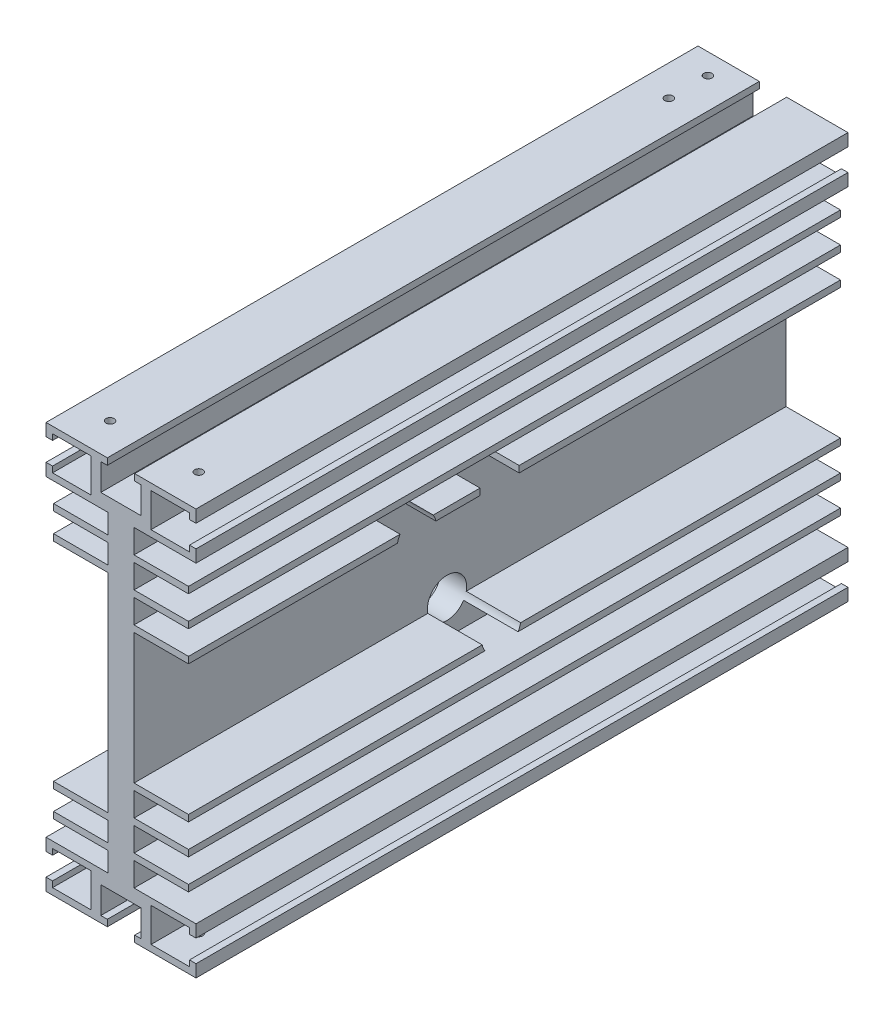
SolidWorks part; units mm, degrees
material "Alumina"
ref_plane "Plano frontal" through (0, 0, 0) normal (0, 0, 1) x (1, 0, 0)
ref_plane "Plano superior" through (0, 0, 0) normal (0, 1, 0) x (1, 0, 0)
ref_plane "Plano direito" through (0, 0, 0) normal (1, 0, 0) x (0, 0, -1)
sketch "Esboço1" plane through (0, 0, 0) normal (0, 0, 1) x (1, 0, 0)
  line L0 (-54.7403, -0.6) -> (-54.7403, 63.2)
  line L1 (-44.5403, -20.8) -> (-44.5403, -29)
  line L2 (-44.5403, -29) -> (-46.5403, -29)
  line L3 (-46.5403, -29) -> (-46.5403, -31)
  line L4 (-46.5403, -31) -> (-27.7403, -31)
  line L5 (-27.7403, -31) -> (-27.7403, -27.2)
  line L6 (-27.7403, -27.2) -> (-29.7403, -27.2)
  line L7 (-29.7403, -27.2) -> (-29.7403, -29)
  line L8 (-29.7403, -29) -> (-41.5403, -29)
  line L9 (-41.5403, -29) -> (-41.5403, -18.6)
  line L10 (-41.5403, -18.6) -> (-29.7403, -18.6)
  line L11 (-29.7403, -18.6) -> (-29.7403, -20.4)
  line L12 (-29.7403, -20.4) -> (-27.7403, -20.4)
  line L13 (-27.7403, -20.4) -> (-27.7403, -16.6)
  line L14 (-27.7403, -16.6) -> (-46.7403, -16.6)
  line L15 (-46.7403, -7.3) -> (-46.7403, 0)
  line L16 (-46.7403, -7.3) -> (-30.0403, -7.3)
  line L17 (-30.0403, -7.3) -> (-30.0403, -9.3)
  line L18 (-30.0403, -9.3) -> (-46.7403, -9.3)
  line L19 (-46.7403, -16.6) -> (-46.7403, -9.3)
  line L20 (-46.7403, 0) -> (-30.0403, 0)
  line L21 (-30.0403, 0) -> (-30.0403, 2)
  line L22 (-30.0403, 2) -> (-46.7403, 2)
  line L23 (-46.7403, 2) -> (-46.7403, 9.3)
  line L24 (-46.7403, 9.3) -> (-30.0403, 9.3)
  line L25 (-30.0403, 9.3) -> (-30.0403, 11.3)
  line L26 (-30.0403, 11.3) -> (-46.7403, 11.3)
  line L27 (-46.7403, 11.3) -> (-46.7403, 51.3)
  line L29 (-56.9403, -20.8) -> (-44.5403, -20.8)
  line L30 (-56.9403, 83.4) -> (-56.9403, 91.6)
  line L31 (-56.9403, 91.6) -> (-54.9403, 91.6)
  line L32 (-54.9403, 91.6) -> (-54.9403, 93.6)
  line L33 (-54.9403, 93.6) -> (-73.7403, 93.6)
  line L34 (-73.7403, 93.6) -> (-73.7403, 89.8)
  line L35 (-71.4403, -0.6) -> (-54.7403, -0.6)
  line L36 (-71.4403, -2.6) -> (-71.4403, -0.6)
  line L37 (-54.7403, -2.6) -> (-71.4403, -2.6)
  line L38 (-54.7403, -16.6) -> (-54.7403, -10.6)
  line L39 (-71.4403, -10.6) -> (-54.7403, -10.6)
  line L40 (-71.4403, -8.6) -> (-71.4403, -10.6)
  line L41 (-54.7403, -8.6) -> (-71.4403, -8.6)
  line L42 (-54.7403, -8.6) -> (-54.7403, -2.6)
  line L43 (-73.7403, -16.6) -> (-54.7403, -16.6)
  line L44 (-73.7403, -20.4) -> (-73.7403, -16.6)
  line L45 (-71.7403, -20.4) -> (-73.7403, -20.4)
  line L46 (-71.7403, -18.6) -> (-71.7403, -20.4)
  line L47 (-59.9403, -18.6) -> (-71.7403, -18.6)
  line L48 (-59.9403, -29) -> (-59.9403, -18.6)
  line L49 (-71.7403, -29) -> (-59.9403, -29)
  line L50 (-71.7403, -27.2) -> (-71.7403, -29)
  line L51 (-73.7403, -27.2) -> (-71.7403, -27.2)
  line L52 (-73.7403, -31) -> (-73.7403, -27.2)
  line L53 (-54.9403, -31) -> (-73.7403, -31)
  line L54 (-54.9403, -29) -> (-54.9403, -31)
  line L55 (-56.9403, -29) -> (-54.9403, -29)
  line L56 (-56.9403, -20.8) -> (-56.9403, -29)
  line L57 (-73.7403, 89.8) -> (-71.7403, 89.8)
  line L58 (-71.7403, 89.8) -> (-71.7403, 91.6)
  line L59 (-71.7403, 91.6) -> (-59.9403, 91.6)
  line L60 (-59.9403, 91.6) -> (-59.9403, 81.2)
  line L61 (-59.9403, 81.2) -> (-71.7403, 81.2)
  line L62 (-71.7403, 81.2) -> (-71.7403, 83)
  line L63 (-71.7403, 83) -> (-73.7403, 83)
  line L64 (-73.7403, 83) -> (-73.7403, 79.2)
  line L65 (-73.7403, 79.2) -> (-54.7403, 79.2)
  line L66 (-54.7403, 71.2) -> (-54.7403, 65.2)
  line L67 (-54.7403, 71.2) -> (-71.4403, 71.2)
  line L68 (-71.4403, 71.2) -> (-71.4403, 73.2)
  line L69 (-71.4403, 73.2) -> (-54.7403, 73.2)
  line L70 (-54.7403, 79.2) -> (-54.7403, 73.2)
  line L71 (-54.7403, 65.2) -> (-71.4403, 65.2)
  line L72 (-71.4403, 65.2) -> (-71.4403, 63.2)
  line L73 (-71.4403, 63.2) -> (-54.7403, 63.2)
  line L74 (-56.9403, 83.4) -> (-44.5403, 83.4)
  line L75 (-30.0403, 51.3) -> (-46.7403, 51.3)
  line L76 (-30.0403, 53.3) -> (-30.0403, 51.3)
  line L77 (-46.7403, 53.3) -> (-30.0403, 53.3)
  line L78 (-46.7403, 60.6) -> (-46.7403, 53.3)
  line L79 (-30.0403, 60.6) -> (-46.7403, 60.6)
  line L80 (-30.0403, 62.6) -> (-30.0403, 60.6)
  line L81 (-46.7403, 62.6) -> (-30.0403, 62.6)
  line L82 (-46.7403, 79.2) -> (-46.7403, 71.9)
  line L83 (-30.0403, 71.9) -> (-46.7403, 71.9)
  line L84 (-30.0403, 69.9) -> (-30.0403, 71.9)
  line L85 (-46.7403, 69.9) -> (-30.0403, 69.9)
  line L86 (-46.7403, 69.9) -> (-46.7403, 62.6)
  line L87 (-27.7403, 79.2) -> (-46.7403, 79.2)
  line L88 (-27.7403, 83) -> (-27.7403, 79.2)
  line L89 (-29.7403, 83) -> (-27.7403, 83)
  line L90 (-29.7403, 81.2) -> (-29.7403, 83)
  line L91 (-41.5403, 81.2) -> (-29.7403, 81.2)
  line L92 (-41.5403, 91.6) -> (-41.5403, 81.2)
  line L93 (-29.7403, 91.6) -> (-41.5403, 91.6)
  line L94 (-29.7403, 89.8) -> (-29.7403, 91.6)
  line L95 (-27.7403, 89.8) -> (-29.7403, 89.8)
  line L96 (-27.7403, 93.6) -> (-27.7403, 89.8)
  line L97 (-46.5403, 93.6) -> (-27.7403, 93.6)
  line L98 (-46.5403, 91.6) -> (-46.5403, 93.6)
  line L99 (-44.5403, 91.6) -> (-46.5403, 91.6)
  line L100 (-44.5403, 83.4) -> (-44.5403, 91.6)
  dimension "D1" = 2
  dimension "D2" = 3.8
  dimension "D3" = 2
  dimension "D4" = 18.8
  dimension "D5" = 3
  dimension "D6" = 2
  dimension "D7" = 2
  dimension "D8" = 2
  dimension "D9" = 3.8
  dimension "D10" = 4.2
  dimension "D11" = 19
  dimension "D12" = 16.7
  dimension "D13" = 7.3
  dimension "D14" = 2
  dimension "D15" = 6
  dimension "D16" = 6
  dimension "D17" = 10.4
  dimension "D18" = 40
  dimension "D19" = 63.8
extrude "Ressalto-extrusão1" add sketch "Esboço1" along normal blind 200
ref_plane "Plano1" through (0, 0, 100) normal (0, 0, 1) x (1, 0, 0)
ref_plane "Plano2" through (0, 31.3, 0) normal (0, -1, 0) x (1, 0, 0)
sketch "Esboço5" plane through (-54.7403, 0, 0) normal (-1, 0, 0) x (0, 0, 1)
  line L3 (200, 93.6) -> (0, 93.6) construction
  line L4 (0, 63.2) -> (0, -0.6) construction
  circle A0 centre (130, 50.1) radius 6.0125
  dimension "D1" = 12.025
  dimension "D2" = 43.5
  dimension "D3" = 130
sketch "Esboço4" plane through (-54.7403, 0, 0) normal (-1, 0, 0) x (0, 0, 1)
  line L0 (200, 93.6) -> (0, 93.6) construction
  line L1 (0, 63.2) -> (0, -0.6) construction
  circle A0 centre (104, 50.1) radius 1.825
  dimension "D1" = 43.5
  dimension "D2" = 104
extrude "Corte-extrusão3" cut sketch "Esboço4" against normal up to next
sketch "Esboço6" plane through (-54.7403, 0, 0) normal (-1, 0, 0) x (0, 0, 1)
  line L0 (0, 63.2) -> (0, -0.6) construction
  line L3 (200, -31) -> (0, -31) construction
  circle A0 centre (104, 12.5) radius 6.0125
  dimension "D1" = 12.025
  dimension "D2" = 43.5
  dimension "D3" = 104
extrude "Corte-extrusão5" cut sketch "Esboço6" against normal up to next
hole_wizard "Broca de rosquear para tarraxa de M3x0.53" positions "Esboço13" profile "Esboço12" hole size "M3x0.5" standard "Métrico Ansi" end condition up to next
sketch "Esboço13" plane through (-54.7403, 0, 0) normal (-1, 0, 0) x (0, 0, 1)
  line L0 (200, 65.2) -> (0, 65.2) construction
  line L1 (0, 63.2) -> (0, -0.6) construction
  line L2 (200, -0.6) -> (0, -0.6) construction
  point P0 (6, 5.9)
  point P1 (6, 58.2)
  dimension "D1" = 7
  dimension "D2" = 6
  dimension "D3" = 6
  dimension "D4" = 6.5
sketch "Esboço12" plane through (-54.7403, 5.9, 6) normal (0, 1, 0) x (0, 0, 1)
  line L0 (0, 0) -> (0, 8)
  line L1 (0, 8) -> (1.25, 8)
  line L2 (1.25, 8) -> (1.25, 0)
  line L5 (1.25, 0) -> (0, 0)
  line L11 (0, -6.35) -> (0, 107.95) construction
  dimension "Thru Hole Dia." = 2.5
  dimension "Thru Hole Depth" = 8
ref_plane "Plano3" through (-46.7403, 51.3, 102.625) normal (0, 0, -1) x (-1, 0, 0)
sketch "Esboço15" plane through (-30.0403, 0, 0) normal (1, 0, 0) x (0, 0, -1)
  line L0 (-200, 53.3) -> (0, 53.3) construction
  line L1 (-110.5666, 51.148) -> (-98.5666, 51.148)
  line L2 (-110.5666, 51.148) -> (-110.5666, 53.3)
  line L3 (-110.5666, 53.3) -> (-98.5666, 53.3)
  line L4 (-98.5666, 51.148) -> (-98.5666, 53.3)
  dimension "D1" = 12
extrude "Corte-extrusão7" cut sketch "Esboço15" against normal up to surface (16.7 mm away) up to face at (-46.7403, 31.8234, 102)
extrude "Corte-extrusão8" cut sketch "Esboço5" against normal up to next
hole_wizard "Broca de rosquear para tarraxa de M3x0.59" positions "Esboço29" profile "Esboço28" hole size "M3x0.5" standard "Métrico Ansi"
sketch "Esboço29" plane through (0, -31, 0) normal (0, -1, 0) x (1, 0, 0)
  point P0 (-64.2861, 189.76)
  point P1 (-37.1403, 189.76)
sketch "Esboço28" plane through (-64.2861, -31, 189.76) normal (1, 0, 0) x (0, 0, -1)
  line L0 (0, 0) -> (0, 2)
  line L1 (0, 2) -> (1.25, 2)
  line L2 (1.25, 2) -> (1.25, 0)
  line L5 (1.25, 0) -> (0, 0)
  line L11 (0, -6.35) -> (0, 107.95) construction
  dimension "Thru Hole Dia." = 2.5
  dimension "Thru Hole Depth" = 2
cosmetic thread "Representação de rosca1" parameters "D2"=3
cosmetic thread "Representação de rosca2" parameters "D2"=3
hole_wizard "Broca de rosquear para tarraxa de M3x0.510" positions "Esboço31" profile "Esboço30" hole size "M3x0.5" standard "Métrico Ansi"
sketch "Esboço31" plane through (0, 93.6, 0) normal (0, 1, 0) x (-1, 0, 0)
  point P0 (37.1403, 189.76)
  point P1 (64.3403, 189.76)
sketch "Esboço30" plane through (-37.1403, 93.6, 189.76) normal (1, 0, 0) x (0, 0, 1)
  line L0 (0, 0) -> (0, 2)
  line L1 (0, 2) -> (1.25, 2)
  line L2 (1.25, 2) -> (1.25, 0)
  line L5 (1.25, 0) -> (0, 0)
  line L11 (0, -6.35) -> (0, 107.95) construction
  dimension "Thru Hole Dia." = 2.5
  dimension "Thru Hole Depth" = 2
cosmetic thread "Representação de rosca3" parameters "D2"=3
cosmetic thread "Representação de rosca4" parameters "D2"=3
hole_wizard "Broca de rosquear para tarraxa de M3x0.511" positions "Esboço33" profile "Esboço32" hole size "M3x0.5" standard "Métrico Ansi"
sketch "Esboço33" plane through (0, -31, 0) normal (0, -1, 0) x (1, 0, 0)
  point P0 (-64.3403, 18.36)
  point P1 (-64.3403, 6.36)
sketch "Esboço32" plane through (-64.3403, -31, 18.36) normal (1, 0, 0) x (0, 0, -1)
  line L0 (0, 0) -> (0, 2)
  line L1 (0, 2) -> (1.25, 2)
  line L2 (1.25, 2) -> (1.25, 0)
  line L5 (1.25, 0) -> (0, 0)
  line L11 (0, -6.35) -> (0, 107.95) construction
  dimension "Thru Hole Dia." = 2.5
  dimension "Thru Hole Depth" = 2
hole_wizard "Broca de rosquear para tarraxa de M3x0.512" positions "Esboço35" profile "Esboço34" hole size "M3x0.5" standard "Métrico Ansi"
sketch "Esboço35" plane through (0, 93.6, 0) normal (0, 1, 0) x (-1, 0, 0)
  point P0 (64.3403, 18.36)
  point P1 (64.3403, 6.36)
sketch "Esboço34" plane through (-64.3403, 93.6, 18.36) normal (1, 0, 0) x (0, 0, 1)
  line L0 (0, 0) -> (0, 2)
  line L1 (0, 2) -> (1.25, 2)
  line L2 (1.25, 2) -> (1.25, 0)
  line L5 (1.25, 0) -> (0, 0)
  line L11 (0, -6.35) -> (0, 107.95) construction
  dimension "Thru Hole Dia." = 2.5
  dimension "Thru Hole Depth" = 2
equation "\"D1@Esboço5\" = \"H_Barra@Inversor3.SLDASM\""
equation "\"D1@Esboço6\"=\"H_Barra@Inversor3.SLDASM\""
equation "\"D2@Esboço4\" = \"Barramento_sy@Inversor3.SLDASM\""
equation "\"D1@Esboço4\" = \"Barramento_gx@Inversor3.SLDASM\""
equation "\"D2@Esboço5\" = \"Barramento_gx@Inversor3.SLDASM\""
equation "\"D3@Esboço5\" = \"Barramento_gy@Inversor3.SLDASM\""
equation "\"D2@Esboço6\" = \"Barramento_sx@Inversor3.SLDASM\""
equation "\"D3@Esboço6\" = \"Barramento_sy@Inversor3.SLDASM\""
